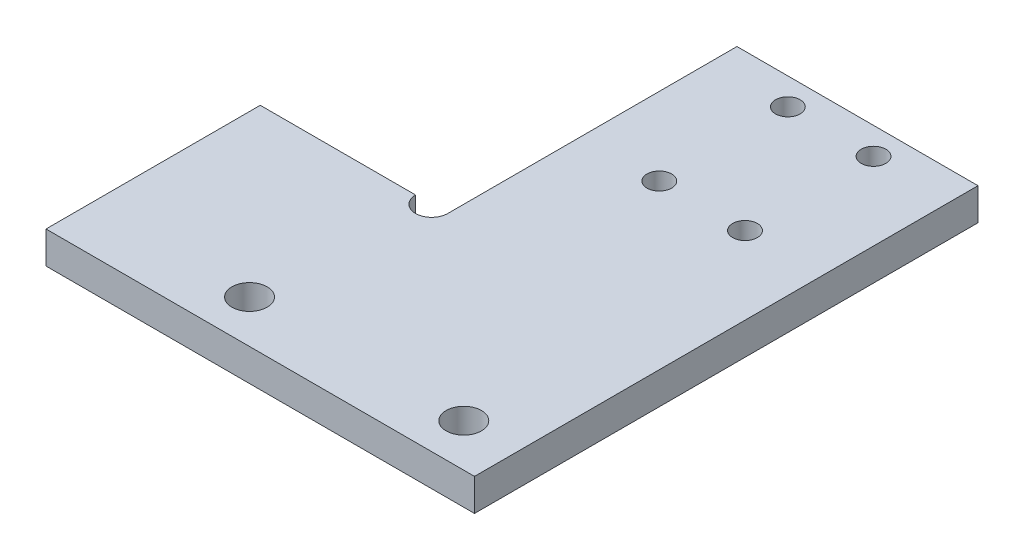
SolidWorks part; units mm, degrees
material "Thornel Mat VMA"
ref_plane "前视基准面" through (0, 0, 0) normal (0, 0, 1) x (1, 0, 0)
ref_plane "上视基准面" through (0, 0, 0) normal (0, 1, 0) x (1, 0, 0)
ref_plane "右视基准面" through (0, 0, 0) normal (1, 0, 0) x (0, 0, -1)
sketch "草图1" plane through (0, 0, 0) normal (0, 1, 0) x (1, 0, 0)
  line L1 (-11.25, 8.5) -> (11.25, 8.5)
  line L2 (-11.25, 8.5) -> (-11.25, -8.5)
  line L3 (-11.25, -8.5) -> (11.25, -8.5)
  line L4 (11.25, 8.5) -> (11.25, -8.5)
  line L5 (-11.25, 8.5) -> (11.25, -8.5) construction
  line L6 (-11.25, -8.5) -> (11.25, 8.5) construction
  point P0 (0, 0)
  dimension "D1" = 22.5
  dimension "D2" = 17
extrude "凸台-拉伸1" add sketch "草图1" along normal blind 3
sketch "草图2" plane through (0, 3, 0) normal (0, 1, 0) x (1, 0, 0)
  line L0 (11.25, 8.5) -> (-11.25, 8.5) construction
  line L1 (-6.75, 8.5) -> (6.75, 8.5)
  line L2 (-6.75, 8.5) -> (-6.75, -8.5)
  line L3 (-6.75, -8.5) -> (6.75, -8.5)
  line L4 (6.75, 8.5) -> (6.75, -8.5)
  line L5 (-11.25, -8.5) -> (11.25, -8.5) construction
  line L6 (11.25, -8.5) -> (11.25, 8.5) construction
  point P10 (4, 6)
  point P11 (-4, 6)
  point P12 (-4, -6)
  point P13 (4, -6)
  dimension "D1" = 13.5
  dimension "D2" = 4.5
  dimension "D3" = 2.5
  dimension "D4" = 2.75
  dimension "D5" = 2.5
  dimension "D6" = 2.5
  dimension "D7" = 2.5
  dimension "D8" = 2.75
  dimension "D9" = 2.75
  dimension "D10" = 2.75
sketch "草图3" plane through (0, 3, 0) normal (0, 1, 0) x (1, 0, 0)
  point P0 (-4, 6)
  point P3 (4, 6)
  point P6 (-4, -6)
  point P9 (4, -6)
hole_wizard "孔1" positions "草图3" profile "草图4" legacy end condition through all
sketch "草图4" plane through (-4, 3, -6) normal (1, 0, 0) x (0, 0, 1)
  line L0 (0, 0) -> (0, 3)
  line L1 (0, 3) -> (1.15, 3)
  line L2 (1.15, 3) -> (1.15, 0)
  line L3 (1.15, 0) -> (0, 0)
  line L4 (0, 110) -> (0, -10) construction
  dimension "直径" = 2.3
  dimension "深度" = 3
sketch "草图5" plane through (0, 3, 0) normal (0, 1, 0) x (1, 0, 0)
  line L0 (-11.25, 8.5) -> (-11.25, -8.5) construction
  line L1 (11.25, -8.5) -> (-11.25, -8.5)
  line L2 (11.25, -8.5) -> (11.25, -38.5)
  line L3 (11.25, -38.5) -> (-11.25, -38.5)
  line L4 (-11.25, -8.5) -> (-11.25, -38.5)
  dimension "D1" = 30
extrude "凸台-拉伸2" add sketch "草图5" against normal blind 3
sketch "草图6" plane through (0, 3, 0) normal (0, 1, 0) x (1, 0, 0)
  line L0 (-11.25, -38.5) -> (11.25, -38.5) construction
  line L1 (-11.25, -38.5) -> (-28.75, -38.5)
  line L2 (-11.25, -38.5) -> (-11.25, -18.5)
  line L3 (-11.25, -18.5) -> (-28.75, -18.5)
  line L4 (-28.75, -38.5) -> (-28.75, -18.5)
  line L5 (-11.25, 8.5) -> (-11.25, -38.5) construction
  line L6 (11.25, -38.5) -> (11.25, 8.5) construction
  dimension "D1" = 20
  dimension "D2" = 40
extrude "凸台-拉伸3" add sketch "草图6" against normal blind 3
sketch "草图7" plane through (0, 3, 0) normal (0, 1, 0) x (1, 0, 0)
  line L0 (-28.75, -38.5) -> (11.25, -38.5) construction
  line L1 (11.25, -38.5) -> (-28.75, -38.5)
  line L2 (11.25, -38.5) -> (11.25, -30.5)
  line L3 (11.25, -30.5) -> (-28.75, -30.5)
  line L4 (-28.75, -38.5) -> (-28.75, -30.5)
  line L6 (11.25, -38.5) -> (11.25, 8.5) construction
  line L7 (-28.75, -34.5) -> (11.25, -34.5)
  point P6 (-13.75, -34.5)
  point P8 (6.25, -34.5)
  dimension "D1" = 8
  dimension "D2" = 40
  dimension "D3" = 5
  dimension "D4" = 20
sketch "草图10" plane through (0, 3, 0) normal (0, 1, 0) x (1, 0, 0)
  point P0 (6.25, -54.5)
  point P2 (-13.75, -54.5)
  point P3 (-13.75, -34.5)
  point P6 (6.25, -34.5)
hole_wizard "孔2" positions "草图10" profile "草图11" legacy end condition through all
sketch "草图11" plane through (6.25, 3, 34.5) normal (1, 0, 0) x (0, 0, 1)
  line L0 (0, 0) -> (0, 3)
  line L1 (0, 3) -> (1.65, 3)
  line L2 (1.65, 3) -> (1.65, 0)
  line L3 (1.65, 0) -> (0, 0)
  line L4 (0, 110) -> (0, -10) construction
  dimension "直径" = 3.3
  dimension "深度" = 3
sketch "草图12" plane through (0, 3, 0) normal (0, 1, 0) x (1, 0, 0)
  line L0 (-11.25, -18.5) -> (-12.75, -18.5)
  line L1 (-11.25, -18.5) -> (-28.75, -18.5) construction
  dimension "D1" = 1.5
sketch "草图15" plane through (0, 3, 0) normal (0, 1, 0) x (1, 0, 0)
sketch "草图17" plane through (0, 3, 0) normal (0, 1, 0) x (1, 0, 0)
  point P0 (-12.75, -18.5)
hole_wizard "孔3" positions "草图17" profile "草图16" legacy end condition up to next
sketch "草图16" plane through (-12.75, 3, 18.5) normal (1, 0, 0) x (0, 0, 1)
  line L0 (0, 0) -> (0, 3)
  line L1 (0, 3) -> (1.5, 3)
  line L2 (1.5, 3) -> (1.5, 0)
  line L3 (1.5, 0) -> (0, 0)
  line L4 (0, 110) -> (0, -10) construction
  dimension "直径" = 3
  dimension "深度" = 3
